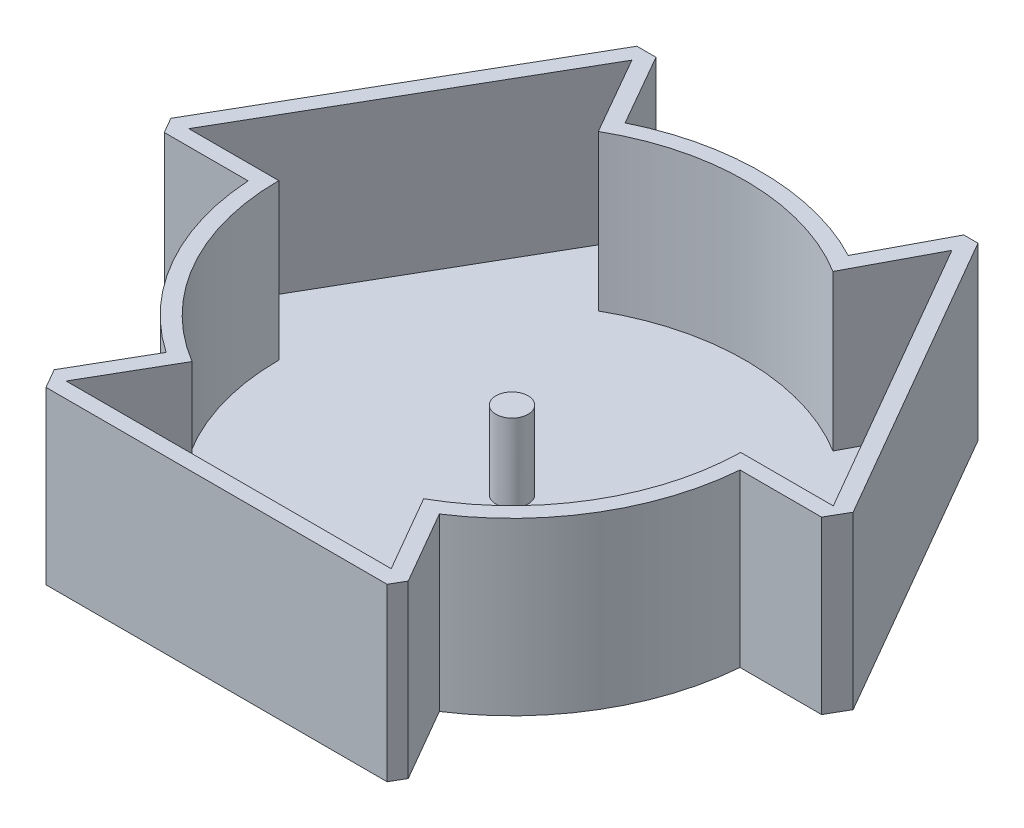
SolidWorks part; units mm, degrees
ref_plane "前视基准面" through (0, 0, 0) normal (0, 0, 1) x (1, 0, 0)
ref_plane "上视基准面" through (0, 0, 0) normal (0, 1, 0) x (1, 0, 0)
ref_plane "右视基准面" through (0, 0, 0) normal (1, 0, 0) x (0, 0, -1)
other "Configuration Table"
sketch "草图2" plane through (0, 0, 0) normal (0, 1, 0) x (1, 0, 0)
  line L0 (-26.3018, 45.884) -> (-18.9561, 33.0496)
  line L1 (53.2141, -0.7294) -> (26.7441, 45.1178)
  line L3 (-26.3018, 45.884) -> (-52.7929, 0)
  line L5 (-27.1161, -45.72) -> (25.987, -45.72)
  line L7 (26.7441, 45.1178) -> (20.0231, 32.4143)
  line L8 (-27.1161, -45.72) -> (-19.5872, -32.6796)
  line L9 (18.7421, -33.1714) -> (25.987, -45.72)
  line L10 (-52.7929, 0) -> (-38.1, 0)
  line L11 (53.2141, -0.7294) -> (38.093, -0.7294)
  line L12 (-42.5051, -17.819) -> (-27.8404, -43.219) [skipped]
  line L13 (42.5051, -17.819) -> (57.1698, 7.581) [skipped]
  line L14 (-5.8209, 45.72) -> (-35.1503, 45.72) [skipped]
  line L15 (-54.2594, -2.54) -> (-40.5605, -2.54)
  line L16 (55.7258, 0) -> (27.8629, 48.26)
  line L17 (27.8629, 48.26) -> (25.533, 48.26)
  line L18 (-27.8629, 48.26) -> (-55.7258, 0)
  line L19 (-55.7258, 0) -> (-54.2594, -2.54)
  line L20 (-27.8629, -48.26) -> (27.8629, -48.26)
  line L21 (27.8629, -48.26) -> (29.1247, -46.0746)
  line L22 (-24.7351, 48.26) -> (-17.975, 36.4487)
  line L23 (25.533, 48.26) -> (19.0054, 35.9222)
  line L24 (40.5083, -3.2694) -> (53.8382, -3.2694)
  line L25 (22.1832, -34.0516) -> (29.1247, -46.0746)
  line L26 (-22.9978, -33.5069) -> (-29.6892, -45.0968)
  line L27 (-29.6892, -45.0968) -> (-27.8629, -48.26)
  line L28 (53.8382, -3.2694) -> (55.7258, 0)
  line L29 (-24.7351, 48.26) -> (-27.8629, 48.26)
  circle A1 centre (0, 0) radius 38.1
  arc A2 (-40.5605, -2.54) -> (-22.9978, -33.5069) centre (0, 0) ccw
  arc A3 (19.0054, 35.9222) -> (-17.975, 36.4487) centre (0, 0) ccw
  arc A4 (22.1832, -34.0516) -> (40.5083, -3.2694) centre (0, 0) ccw
  arc A7 (26.0393, -45.8106) -> (28.2169, -44.5023) centre (0, 0) ccw construction
  dimension "D2" = 76.2
  dimension "D3" = 81.28
  dimension "D5" = 2.54
  dimension "D6" = 2.54
  dimension "D7" = 2.54
  dimension "D8" = 2.54
  dimension "D9" = 2.54
  dimension "D10" = 2.54
  dimension "D11" = 2.54
extrude "凸台-拉伸2" add sketch "草图2" along normal blind 25.4 contours L25 A4 L24 L28 L16 L17 L23 A3 L22 L29 L18 L19 L15 A2 L26 L27 L20 L21 A1 L9 L5 L8 L10 L3 L0 L7 L1 L11
sketch "草图3" plane through (0, 0, 0) normal (0, -1, 0) x (1, 0, 0)
  line L15 (22.1832, 34.0516) -> (29.1247, 46.0746)
  line L16 (29.1247, 46.0746) -> (27.8629, 48.26)
  line L17 (27.8629, 48.26) -> (-27.8629, 48.26)
  line L18 (-27.8629, 48.26) -> (-29.6892, 45.0968)
  line L19 (-29.6892, 45.0968) -> (-22.9978, 33.5069)
  line L20 (-40.5605, 2.54) -> (-54.2594, 2.54)
  line L21 (-54.2594, 2.54) -> (-55.7258, 0)
  line L22 (-55.7258, 0) -> (-27.8629, -48.26)
  line L23 (-27.8629, -48.26) -> (-24.7351, -48.26)
  line L24 (-24.7351, -48.26) -> (-17.975, -36.4487)
  line L25 (19.0054, -35.9222) -> (25.533, -48.26)
  line L26 (25.533, -48.26) -> (27.8629, -48.26)
  line L27 (27.8629, -48.26) -> (55.7258, 0)
  line L28 (55.7258, 0) -> (53.8382, 3.2694)
  line L29 (53.8382, 3.2694) -> (40.5083, 3.2694)
  line L30 (22.1832, 34.0516) -> (29.1247, 46.0746)
  line L31 (29.1247, 46.0746) -> (27.8629, 48.26)
  line L32 (27.8629, 48.26) -> (-27.8629, 48.26)
  line L33 (-27.8629, 48.26) -> (-29.6892, 45.0968)
  line L34 (-29.6892, 45.0968) -> (-22.9978, 33.5069)
  line L35 (-40.5605, 2.54) -> (-54.2594, 2.54)
  line L36 (-54.2594, 2.54) -> (-55.7258, 0)
  line L37 (-55.7258, 0) -> (-27.8629, -48.26)
  line L38 (-27.8629, -48.26) -> (-24.7351, -48.26)
  line L39 (-24.7351, -48.26) -> (-17.975, -36.4487)
  line L40 (19.0054, -35.9222) -> (25.533, -48.26)
  line L41 (25.533, -48.26) -> (27.8629, -48.26)
  line L42 (27.8629, -48.26) -> (55.7258, 0)
  line L43 (55.7258, 0) -> (53.8382, 3.2694)
  line L44 (53.8382, 3.2694) -> (40.5083, 3.2694)
  arc A3 (-22.9978, 33.5069) -> (-40.5605, 2.54) centre (0, 0) ccw
  arc A4 (-17.975, -36.4487) -> (19.0054, -35.9222) centre (0, 0) ccw
  arc A5 (40.5083, 3.2694) -> (22.1832, 34.0516) centre (0, 0) ccw
  arc A6 (-22.9978, 33.5069) -> (-40.5605, 2.54) centre (0, 0) ccw
  arc A7 (-17.975, -36.4487) -> (19.0054, -35.9222) centre (0, 0) ccw
  arc A8 (40.5083, 3.2694) -> (22.1832, 34.0516) centre (0, 0) ccw
  dimension "D1" = 0
extrude "凸台-拉伸4" add sketch "草图3" along normal blind 2.54
sketch "草图4" plane through (0, 0, 0) normal (0, 1, 0) x (1, 0, 0)
  circle A0 centre (0, 0) radius 2.6236
extrude "凸台-拉伸5" add sketch "草图4" along normal blind 12.7
